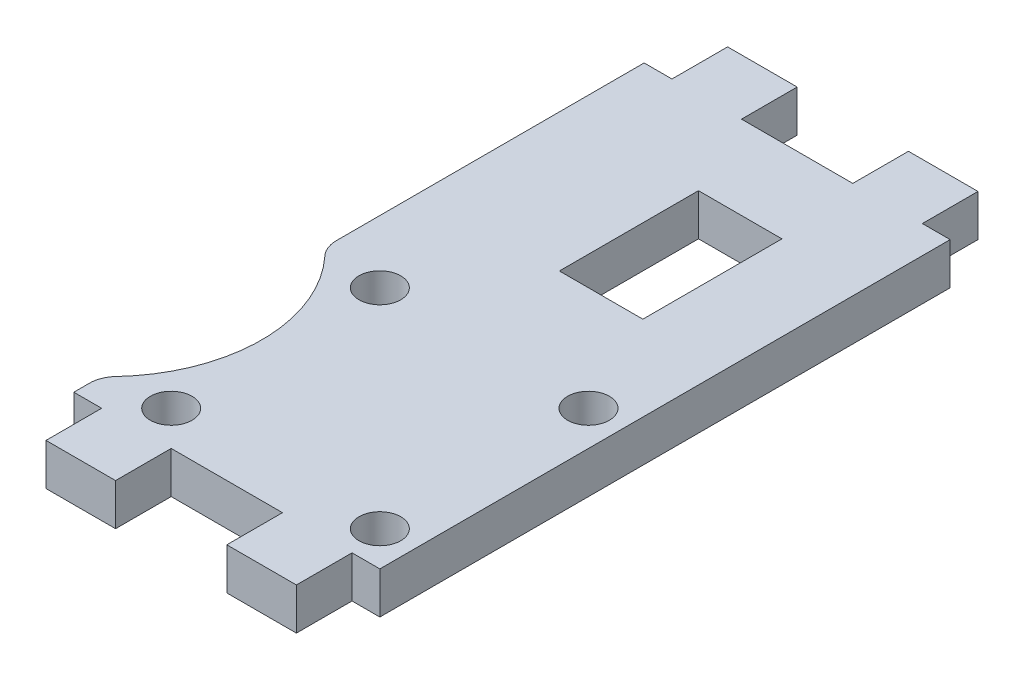
SolidWorks part; units mm, degrees
ref_plane "Front Plane" through (0, 0, 0) normal (0, 0, 1) x (1, 0, 0)
ref_plane "Top Plane" through (0, 0, 0) normal (0, 1, 0) x (1, 0, 0)
ref_plane "Right Plane" through (0, 0, 0) normal (1, 0, 0) x (0, 0, -1)
sketch "草图1" plane through (0, 0, 0) normal (0, 1, 0) x (1, 0, 0)
  line L1 (-11, -20.5) -> (11, -20.5)
  line L2 (-11, -20.5) -> (-11, 20.5)
  line L3 (-11, 20.5) -> (11, 20.5)
  line L4 (11, -20.5) -> (11, 20.5)
  line L5 (-11, -20.5) -> (11, 20.5) construction
  line L6 (-11, 20.5) -> (11, -20.5) construction
  point P0 (0, 0)
  dimension "D1" = 22
  dimension "D2" = 41
extrude "凸台-拉伸1" add sketch "草图1" along normal blind 3
sketch "草图2" plane through (0, 3, 0) normal (0, 1, 0) x (1, 0, 0)
  line L0 (0, 20.5) -> (0, -5.979) construction
  line L1 (11, 20.5) -> (-11, 20.5) construction
  line L2 (-11, 20.5) -> (-11, -20.5) construction
  line L3 (-9, 20.5) -> (-4, 20.5)
  line L4 (-9, 20.5) -> (-9, 24.5)
  line L5 (-9, 24.5) -> (-4, 24.5)
  line L6 (-4, 20.5) -> (-4, 24.5)
  line L7 (-9, 20.5) -> (-4, 24.5) construction
  line L8 (-9, 24.5) -> (-4, 20.5) construction
  line L9 (11, -20.5) -> (11, 20.5) construction
  line L10 (4, 20.5) -> (9, 20.5)
  line L11 (4, 20.5) -> (4, 24.5)
  line L12 (4, 24.5) -> (9, 24.5)
  line L13 (9, 20.5) -> (9, 24.5)
  line L14 (4, 20.5) -> (9, 24.5) construction
  line L15 (4, 24.5) -> (9, 20.5) construction
  line L16 (-23.7416, 0) -> (24.3621, 0) construction
  line L17 (4, -24.5) -> (9, -20.5) construction
  line L18 (4, -20.5) -> (9, -24.5) construction
  line L19 (-9, -24.5) -> (-4, -20.5) construction
  line L20 (-9, -20.5) -> (-4, -24.5) construction
  line L21 (9, -20.5) -> (9, -24.5)
  line L22 (4, -24.5) -> (9, -24.5)
  line L23 (4, -20.5) -> (4, -24.5)
  line L24 (4, -20.5) -> (9, -20.5)
  line L25 (-4, -20.5) -> (-4, -24.5)
  line L26 (-9, -24.5) -> (-4, -24.5)
  line L27 (-9, -20.5) -> (-9, -24.5)
  line L28 (-9, -20.5) -> (-4, -20.5)
  point P9 (-6.5, 22.5)
  point P16 (6.5, 22.5)
  point P29 (6.5, -22.5)
  point P30 (-6.5, -22.5)
  dimension "D1" = 4
  dimension "D2" = 5
  dimension "D3" = 2
  dimension "D4" = 5
  dimension "D5" = 2
  dimension "D6" = 4
extrude "凸台-拉伸2" add sketch "草图2" against normal up to surface (3 mm away) up to face at (0, 0, 0)
sketch "草图3" plane through (0, 0, 0) normal (0, -1, 0) x (1, 0, 0)
  line L1 (0.0563, -11.9) -> (3.7561, -11.9) construction
  line L2 (0.0563, -11.9) -> (0.0563, -7.1) construction
  line L3 (0.0563, -7.1) -> (3.7561, -7.1) construction
  line L4 (3.7561, -11.9) -> (3.7561, -7.1) construction
  line L5 (0.0563, -11.9) -> (3.7561, -7.1) construction
  line L6 (0.0563, -7.1) -> (3.7561, -11.9) construction
  line L7 (4.9062, -14.5) -> (-1.0938, -14.5)
  line L8 (4.9062, -14.5) -> (4.9062, -4.5)
  line L9 (4.9062, -4.5) -> (-1.0938, -4.5)
  line L10 (-1.0938, -14.5) -> (-1.0938, -4.5)
  line L11 (4.9062, -14.5) -> (-1.0938, -4.5) construction
  line L12 (4.9062, -4.5) -> (-1.0938, -14.5) construction
  point P4 (1.9062, -9.5)
  point P7 (1.9062, -9.5)
  dimension "D1" = 10
  dimension "D2" = 6
extrude "切除-拉伸1" cut sketch "草图3" against normal blind 10
sketch "草图4" plane through (0, 0, 0) normal (0, -1, 0) x (1, 0, 0)
  line L0 (-13.8792, 18) -> (13.9347, 18) construction
  line L1 (-11, 20.5) -> (-9, 20.5) construction
  line L3 (-6.5, 3) -> (-6.5, 18) construction
  line L4 (11, 20.5) -> (11, -20.5) construction
  circle A0 centre (-6.5, 18) radius 1.5
  circle A1 centre (8.5, 18) radius 1.5
  circle A2 centre (-6.5, 3) radius 1.5
  circle A3 centre (8.5, 3) radius 1.5
  dimension "D2" = 3
  dimension "D3" = 3
  dimension "D4" = 15
  dimension "D5" = 3
  dimension "D6" = 15
  dimension "D7" = 2.5
  dimension "D8" = 3
  dimension "D9" = 15
  dimension "D10" = 15
  dimension "D1" = 2.5
extrude "切除-拉伸2" cut sketch "草图4" against normal blind 10
sketch "草图5" plane through (0, 0, 0) normal (0, -1, 0) x (1, 0, 0)
  line L0 (-6.5, 3) -> (-6.5, 18) construction
  line L1 (-6.5, 10.5) -> (11.9339, 10.5) construction
  circle A0 centre (-18.5, 10.5) radius 11
  dimension "D1" = 22
  dimension "D2" = 12
extrude "切除-拉伸3" cut sketch "草图5" against normal blind 10
fillet "圆角1" radius 2 2 edges at (-11, 1.5, 2.4533) (-11, 1.5, 18.5467)
